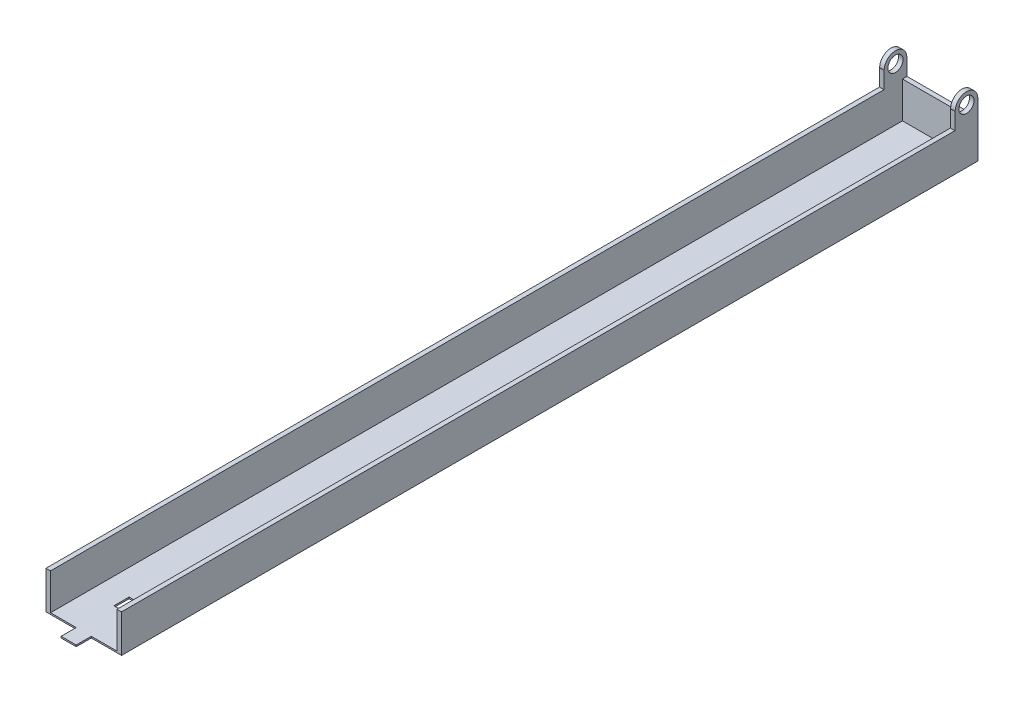
SolidWorks part; units mm, degrees
ref_plane "Front Plane" through (0, 0, 0) normal (0, 0, 1) x (1, 0, 0)
ref_plane "Top Plane" through (0, 0, 0) normal (0, 1, 0) x (1, 0, 0)
ref_plane "Right Plane" through (0, 0, 0) normal (1, 0, 0) x (0, 0, -1)
sketch "Sketch1" plane through (0, 0, 0) normal (0, 0, 1) x (1, 0, 0)
  line L1 (-6.35, 3.175) -> (6.35, 3.175)
  line L2 (-6.35, 3.175) -> (-6.35, -3.175)
  line L3 (-6.35, -3.175) -> (6.35, -3.175)
  line L4 (6.35, 3.175) -> (6.35, -3.175)
  line L5 (-6.35, 3.175) -> (6.35, -3.175) construction
  line L6 (-6.35, -3.175) -> (6.35, 3.175) construction
  point P0 (0, 0)
  dimension "D1" = 6.35
  dimension "D2" = 12.7
extrude "Boss-Extrude1" add sketch "Sketch1" against normal blind 144.78
sketch "Sketch2" plane through (0, 3.175, 0) normal (0, 1, 0) x (1, 0, 0)
  line L4 (-6.35, 144.78) -> (-6.35, 0) construction
  line L5 (0, 0) -> (0, 0.381) construction
  line L7 (5.588, 0.381) -> (-5.588, 0.381)
  line L10 (-5.588, 0.381) -> (-5.588, 0.762)
  line L13 (5.588, 0.762) -> (5.588, 144.018)
  line L14 (5.588, 144.018) -> (-5.588, 144.018)
  line L15 (-5.588, 144.018) -> (-5.588, 0.762)
  line L16 (5.588, 0.762) -> (5.588, 0.381)
  point P9 (0, 0.381)
  dimension "D2" = 0.762
  dimension "D1" = 0.381
extrude "Cut-Extrude1" cut sketch "Sketch2" against normal blind 6.096
sketch "Sketch3" plane through (6.35, 0, 0) normal (1, 0, 0) x (0, 0, -1)
  line L0 (144.78, 3.175) -> (144.78, 5.9795)
  line L1 (144.78, 5.9795) -> (144.7491, 5.9795)
  line L2 (140.9082, 5.9795) -> (140.9082, 3.175)
  line L3 (144.78, 3.175) -> (0, 3.175) construction
  line L4 (140.9082, 3.175) -> (144.78, 3.175)
  line L5 (140.9391, 5.9795) -> (140.9082, 5.9795)
  circle A0 centre (142.8441, 5.9795) radius 1.27
  arc A1 (144.7491, 5.9795) -> (140.9391, 5.9795) centre (142.8441, 5.9795) ccw
  circle A2 centre (142.8441, 5.9795) radius 1.905 construction
  dimension "D1" = 2.54
  dimension "D2" = 0.635
extrude "Boss-Extrude2" add sketch "Sketch3" against normal blind 0.762
sketch "Sketch4" plane through (0, -2.921, 0) normal (0, 1, 0) x (1, 0, 0)
  line L0 (0, -185.1752) -> (0, 185.9372) construction
  point P3 (0, 0.381)
ref_plane "Plane1" through (0, 0, 0) normal (1, 0, 0) x (0, 0, -1)
mirror "Mirror1" about plane through (0, 0, 0) normal (1, 0, 0) of "Boss-Extrude2"
sketch "Sketch5" plane through (0, 0, 0) normal (0, 0, 1) x (1, 0, 0)
  line L1 (-6.35, -3.175) -> (6.35, -3.175)
  line L2 (-6.35, -3.175) -> (-6.35, 3.175)
  line L3 (-6.35, 3.175) -> (6.35, 3.175)
  line L4 (6.35, -3.175) -> (6.35, 3.175)
  line L5 (-6.35, -3.175) -> (6.35, 3.175) construction
  line L6 (-6.35, 3.175) -> (6.35, -3.175) construction
  point P0 (0, 0)
extrude "Cut-Extrude2" cut sketch "Sketch5" against normal blind 0.762
sketch "Sketch6" plane through (0, 0, -0.762) normal (0, 0, 1) x (1, 0, 0)
  line L0 (0, -2.921) -> (0, -3.175) construction
  line L2 (-6.35, -3.175) -> (6.35, -3.175) construction
  line L4 (-1.27, -2.921) -> (1.27, -2.921)
  line L5 (-1.27, -2.921) -> (-1.27, -3.175)
  line L6 (-1.27, -3.175) -> (1.27, -3.175)
  line L7 (1.27, -2.921) -> (1.27, -3.175)
  line L8 (-1.27, -2.921) -> (1.27, -3.175) construction
  line L9 (-1.27, -3.175) -> (1.27, -2.921) construction
  point P5 (0, -3.048)
  dimension "D1" = 2.54
extrude "Boss-Extrude3" add sketch "Sketch6" along normal blind 2.54
sketch "Sketch8" plane through (0, -2.921, 0) normal (0, 1, 0) x (1, 0, 0)
  line L0 (0, -1.778) -> (0, 8.382) construction
  line L1 (1.27, -1.778) -> (-1.27, -1.778) construction
  line L2 (0, -185.1752) -> (0, 185.9372) construction
  line L4 (-1.27, 9.652) -> (1.27, 9.652)
  line L5 (-1.27, 9.652) -> (-1.27, 7.112)
  line L6 (-1.27, 7.112) -> (1.27, 7.112)
  line L7 (1.27, 9.652) -> (1.27, 7.112)
  line L8 (-1.27, 9.652) -> (1.27, 7.112) construction
  line L9 (-1.27, 7.112) -> (1.27, 9.652) construction
  dimension "D1" = 10.16
  dimension "D2" = 2.54
  dimension "D3" = 2.54
extrude "Cut-Extrude3" cut sketch "Sketch8" against normal blind 2.54
